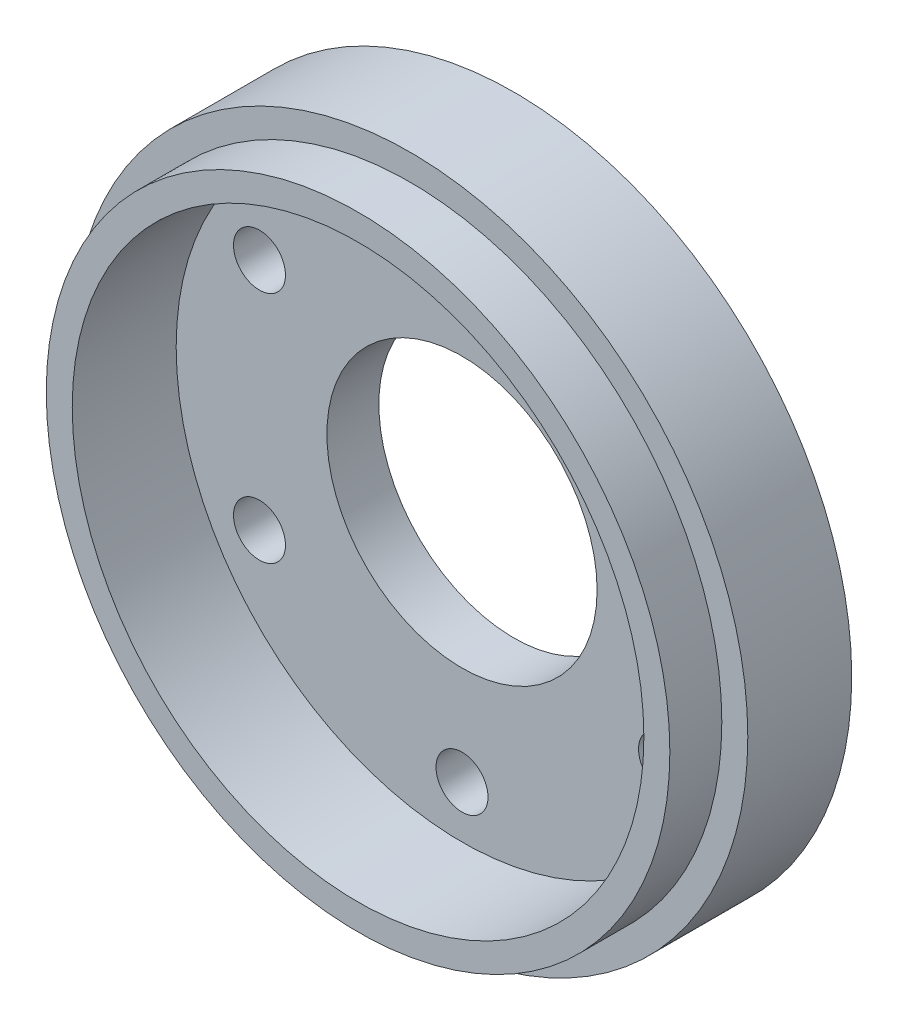
SolidWorks part; units mm, degrees
material "6061 合金"
ref_plane "前视基准面" through (0, 0, 0) normal (0, 0, 1) x (1, 0, 0)
ref_plane "上视基准面" through (0, 0, 0) normal (0, 1, 0) x (1, 0, 0)
ref_plane "右视基准面" through (0, 0, 0) normal (1, 0, 0) x (0, 0, -1)
other "Configuration Table"
sketch "草图1" plane through (0, 0, 0) normal (0, 0, 1) x (1, 0, 0)
  circle A0 centre (0, 0) radius 13
  circle A1 centre (0, 0) radius 32.5
  dimension "D1" = 26
  dimension "D2" = 65
extrude "凸台-拉伸1" add sketch "草图1" along normal blind 5
sketch "草图2" plane through (0, 0, 5) normal (0, 0, 1) x (1, 0, 0)
  circle A0 centre (0, 0) radius 27.5
  circle A1 centre (0, 0) radius 32.5
  dimension "D1" = 55
  dimension "D2" = 65
extrude "凸台-拉伸2" add sketch "草图2" along normal blind 5
sketch "草图3" plane through (0, 0, 5) normal (0, 0, 1) x (1, 0, 0)
  circle A0 centre (0, 0) radius 22.5 construction
  circle A1 centre (0, 22.5) radius 2.5
  circle A2 centre (19.4856, 11.25) radius 2.5
  circle A3 centre (19.4856, -11.25) radius 2.5
  circle A4 centre (0, -22.5) radius 2.5
  circle A5 centre (-19.4856, -11.25) radius 2.5
  circle A6 centre (-19.4856, 11.25) radius 2.5
  point P17 (0, 0)
  dimension "D1" = 45
  dimension "D2" = 5
  dimension "D3" = 6
extrude "切除-拉伸1" cut sketch "草图3" against normal through all
cosmetic thread "装饰螺纹线1" parameters "D2"=6
cosmetic thread "装饰螺纹线2" parameters "D2"=6
cosmetic thread "装饰螺纹线3" parameters "D2"=6
cosmetic thread "装饰螺纹线4" parameters "D2"=6
cosmetic thread "装饰螺纹线5" parameters "D2"=6
cosmetic thread "装饰螺纹线6" parameters "D2"=6
sketch "草图4" plane through (0, 0, 10) normal (0, 0, 1) x (1, 0, 0)
  circle A0 centre (0, 0) radius 30
  circle A1 centre (0, 0) radius 27.5
  dimension "D1" = 60
  dimension "D2" = 55
extrude "凸台-拉伸3" add sketch "草图4" along normal blind 5
